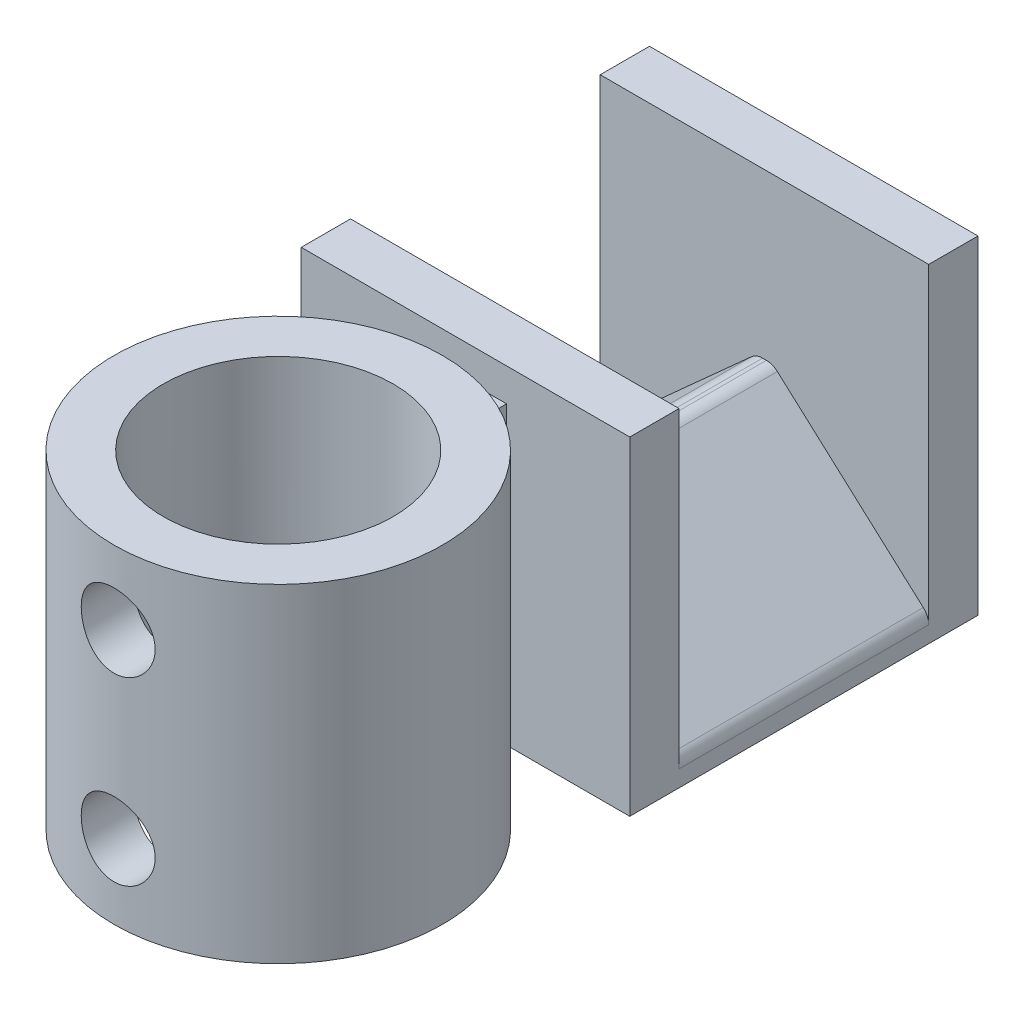
SolidWorks part; units mm, degrees
material "ABS"
ref_plane "Front Plane" through (0, 0, 0) normal (0, 0, 1) x (1, 0, 0)
ref_plane "Top Plane" through (0, 0, 0) normal (0, 1, 0) x (1, 0, 0)
ref_plane "Right Plane" through (0, 0, 0) normal (1, 0, 0) x (0, 0, -1)
sketch "Sketch2" plane through (0, 0, 0) normal (0, 0, 1) x (1, 0, 0)
  line L1 (-10, -5) -> (10, -5)
  line L2 (-10, -5) -> (-10, 5)
  line L3 (-10, 5) -> (10, 5)
  line L4 (10, -5) -> (10, 5)
  line L5 (-10, -5) -> (10, 5) construction
  line L6 (-10, 5) -> (10, -5) construction
  point P0 (0, 0)
  dimension "D1" = 10
  dimension "D2" = 20
extrude "Boss-Extrude1" add sketch "Sketch2" along normal mid plane 15.2
chamfer "Chamfer1" distance 9.5 angle 42 2 edges at (10, 5, 0) (-10, 5, 0)
fillet "Fillet3" radius 1 4 edges at (-10, -3.5538, 0) (10, -3.5538, 0) (0.5, 5, 0) (-0.5, 5, 0)
sketch "Sketch3" plane through (0, 0, 7.6) normal (0, 0, 1) x (1, 0, 0)
  line L0 (-10, -5) -> (10, -5) construction
  line L1 (-10, 15) -> (10, 15)
  line L2 (-10, 15) -> (-10, -5)
  line L3 (-10, -5) -> (10, -5)
  line L4 (10, 15) -> (10, -5)
  line L5 (-10, 15) -> (10, -5) construction
  line L6 (-10, -5) -> (10, 15) construction
  point P0 (0, 5)
  dimension "D1" = 20
  dimension "D2" = 20
extrude "Boss-Extrude2" add sketch "Sketch3" along normal blind 3
mirror "Mirror1" about plane through (0, 0, 0) normal (0, 0, 1) of "Boss-Extrude2"
sketch "Sketch6" plane through (0, 0, 0) normal (0, 1, 0) x (1, 0, 0)
  circle A0 centre (0, -22) radius 10
  circle A1 centre (0, -22) radius 7
  dimension "D1" = 14
  dimension "D2" = 3
  dimension "D3" = 22
extrude "Boss-Extrude3" add sketch "Sketch6" along normal up to surface and the other way up to surface separate body up to face at (0, 15, 9.1) other way up to face at (0, -5, 0)
sketch "Sketch5" plane through (0, 0, 10.6) normal (0, 0, 1) x (1, 0, 0)
  line L0 (-10, -5) -> (10, -5) construction
  line L1 (-2.5, 13) -> (2.5, 13)
  line L2 (-2.5, 13) -> (-2.5, -3)
  line L3 (-2.5, -3) -> (2.5, -3)
  line L4 (2.5, 13) -> (2.5, -3)
  line L5 (-2.5, 13) -> (2.5, -3) construction
  line L6 (-2.5, -3) -> (2.5, 13) construction
  line L7 (10, 15) -> (-10, 15) construction
  point P0 (0, 5)
  dimension "D1" = 2
  dimension "D2" = 2
  dimension "D3" = 5
extrude "Boss-Extrude4" add sketch "Sketch5" along normal up to surface (4.8617 mm away)
ref_plane "Plane1" through (0, 0, 20) normal (0, 0, 1) x (1, 0, 0)
sketch "Sketch7" plane through (0, 0, 20) normal (0, 0, 1) x (1, 0, 0)
  line L2 (-10, -5) -> (10, -5) construction
  line L3 (7, 15) -> (-7, 15) construction
  circle A0 centre (0, 10.5) radius 2.25
  circle A1 centre (0, -0.5) radius 2.25
  dimension "D1" = 4.5
  dimension "D2" = 4.5
  dimension "D3" = 4.5
  dimension "D4" = 4.5
extrude "Cut-Extrude1" cut sketch "Sketch7" along normal up to surface (11.7436 mm away)
equation "\"BEAM_WIDTH\"= 15.2mm"
equation "\"D1@Boss-Extrude1\"=\"BEAM_WIDTH\""
